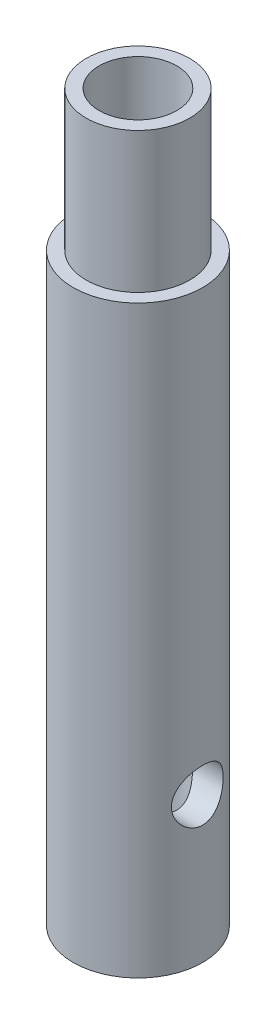
SolidWorks part; units mm, degrees
ref_plane "Plano frontal" through (0, 0, 0) normal (0, 0, 1) x (1, 0, 0)
ref_plane "Plano superior" through (0, 0, 0) normal (0, 1, 0) x (1, 0, 0)
ref_plane "Plano direito" through (0, 0, 0) normal (1, 0, 0) x (0, 0, -1)
sketch "Esboço1" plane through (0, 0, 0) normal (0, 1, 0) x (1, 0, 0)
  circle A0 centre (0, 0) radius 12.5
  dimension "D1" = 25
extrude "Ressalto-extrusão1" add sketch "Esboço1" along normal blind 112.9
sketch "Esboço2" plane through (0, 112.9, 0) normal (0, 1, 0) x (1, 0, 0)
  circle A0 centre (0, 0) radius 10
  dimension "D1" = 20
extrude "Ressalto-extrusão2" add sketch "Esboço2" along normal blind 27.1
sketch "Esboço3" plane through (0, 140, 0) normal (0, 1, 0) x (1, 0, 0)
  circle A0 centre (0, 0) radius 7.5
  dimension "D1" = 15
extrude "Corte-extrusão1" cut sketch "Esboço3" against normal through all
sketch "Esboço5" plane through (0, 0, 0) normal (1, 0, 0) x (0, 0, -1)
  line L0 (-12.5, 0) -> (12.5, 0) construction
  circle A2 centre (0, 28) radius 5
  dimension "D1" = 10
  dimension "D2" = 28
extrude "Corte-extrusão2" cut sketch "Esboço5" against normal mid plane 30
